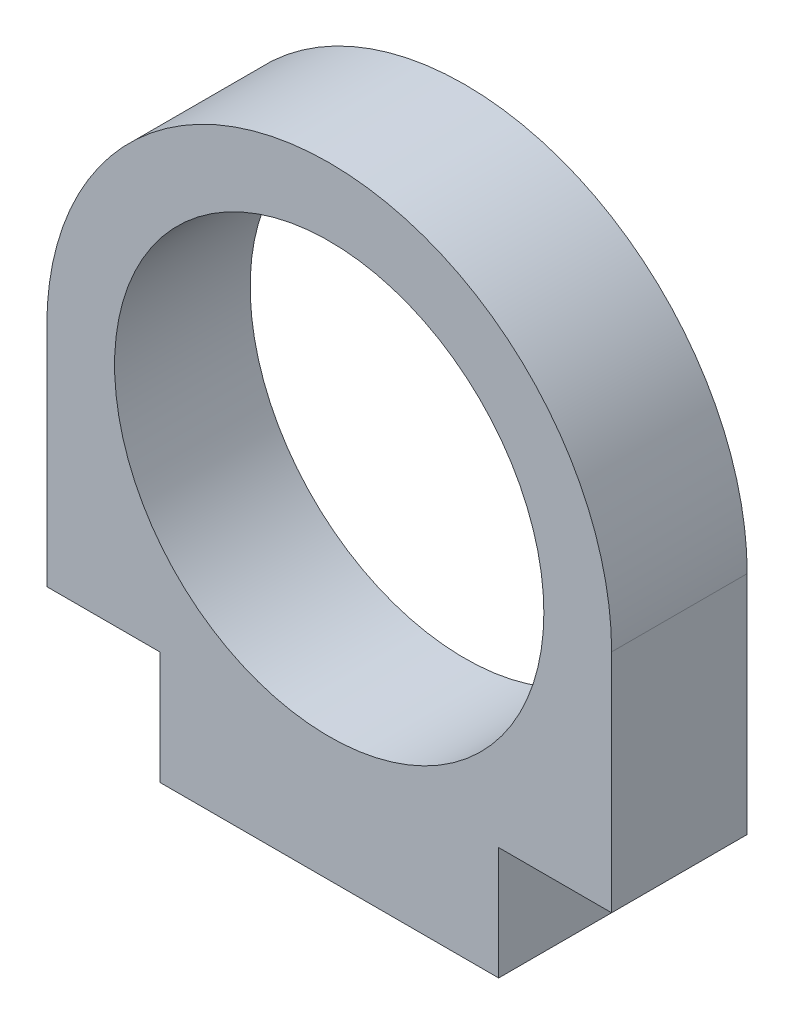
SolidWorks part; units mm, degrees
ref_plane "Alzado" through (0, 0, 0) normal (0, 0, 1) x (1, 0, 0)
ref_plane "Planta" through (0, 0, 0) normal (0, 1, 0) x (1, 0, 0)
ref_plane "Vista lateral" through (0, 0, 0) normal (1, 0, 0) x (0, 0, -1)
sketch "Croquis1" plane through (0, 0, 0) normal (0, 0, 1) x (1, 0, 0)
  line L0 (-12.5, -10) -> (12.5, -10) construction
  line L2 (-12.5, 0) -> (-12.5, -15)
  line L3 (-12.5, -15) -> (12.5, -15)
  line L4 (12.5, 0) -> (12.5, -15)
  line L6 (-12.5, -10) -> (-7.5, -10)
  line L7 (-12.5, -10) -> (-12.5, -15)
  line L8 (-12.5, -15) -> (-7.5, -15)
  line L9 (-7.5, -10) -> (-7.5, -15)
  line L10 (12.5, -10) -> (7.5, -10)
  line L11 (12.5, -10) -> (12.5, -15)
  line L12 (12.5, -15) -> (7.5, -15)
  line L13 (7.5, -10) -> (7.5, -15)
  arc A0 (12.5, 0) -> (-12.5, 0) centre (0, 0) ccw
  circle A1 centre (0, 0) radius 9.5
  point P13 (7.5, -12.5)
  dimension "D2" = 19
  dimension "D4" = 12.5
  dimension "D1" = 25
  dimension "D3" = 15
  dimension "D5" = 5
  dimension "D6" = 5
  dimension "D7" = 5
extrude "Saliente-Extruir1" add sketch "Croquis1" along normal blind 6 contours L6 L0 L10 L4 A0 L2 A1 | L0 L9 L3 L13
